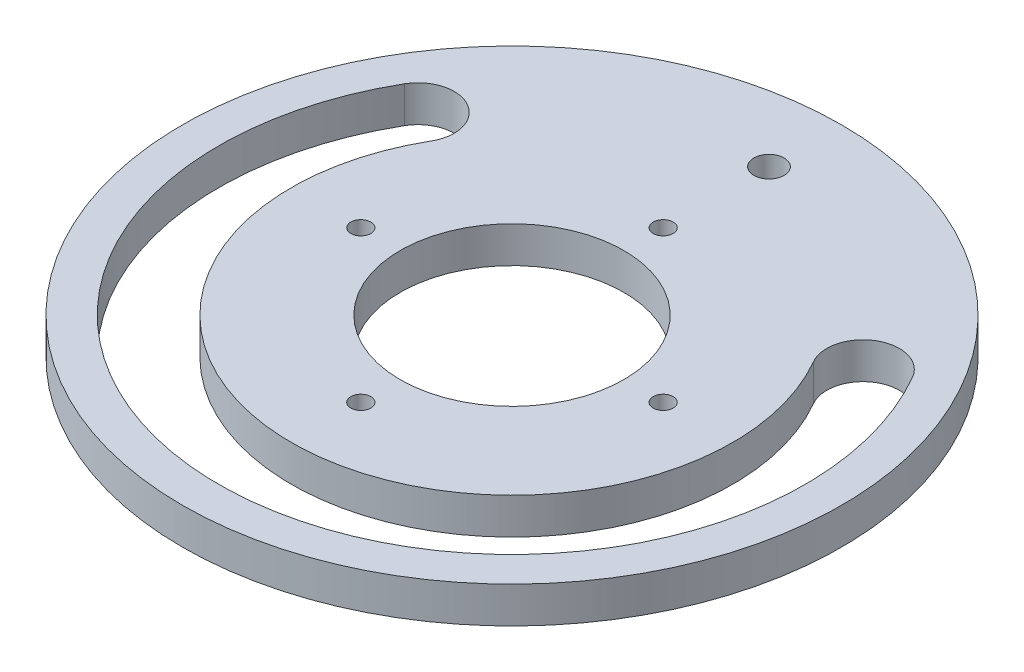
SolidWorks part; units mm, degrees
ref_plane "Спереди" through (0, 0, 0) normal (0, 0, 1) x (1, 0, 0)
ref_plane "Сверху" through (0, 0, 0) normal (0, 1, 0) x (1, 0, 0)
ref_plane "Справа" through (0, 0, 0) normal (1, 0, 0) x (0, 0, -1)
sketch "Эскиз1" plane through (0, 0, 0) normal (0, 1, 0) x (1, 0, 0)
  circle A0 centre (0, 0) radius 54.5
  dimension "D1" = 109
extrude "Бобышка-Вытянуть1" add sketch "Эскиз1" along normal blind 6
sketch "Эскиз2" plane through (0, 6, 0) normal (0, 1, 0) x (1, 0, 0)
  line L0 (0, 0) -> (0, -54.5) construction
  line L1 (0, 0) -> (-54.5, 0) construction
  line L2 (-54.5, 0) -> (54.5, 0) construction
  line L3 (0, 0) -> (-36.8061, 21.25) construction
  line L4 (0, 54.5) -> (0, 0) construction
  line L5 (0, 0) -> (36.8061, 21.25) construction
  circle A0 centre (0, 0) radius 42.5 construction
  circle A1 centre (0, 0) radius 54.5 construction
  arc A2 (-42.0022, 24.25) -> (42.0022, 24.25) centre (0, 0) ccw
  arc A3 (-31.6099, 18.25) -> (31.6099, 18.25) centre (0, 0) ccw
  circle A4 centre (0, 42.5) radius 2.5
  arc A5 (-31.6099, 18.25) -> (-42.0022, 24.25) centre (-36.8061, 21.25) ccw
  arc A6 (42.0022, 24.25) -> (31.6099, 18.25) centre (36.8061, 21.25) ccw
  dimension "D1" = 85
  dimension "D2" = 5
  dimension "D3" = 97
  dimension "D4" = 73
  dimension "D7" = 12
  dimension "D8" = 12
  dimension "D5" = 120
  dimension "D6" = 60
extrude "Вырез-Вытянуть1" cut sketch "Эскиз2" against normal blind 6
sketch "Эскиз3" plane through (0, 6, 0) normal (0, 1, 0) x (1, 0, 0)
  line L0 (0, 54.5) -> (0, -54.5) construction
  line L1 (0, -54.5) -> (54.5, 0) construction
  line L2 (54.5, 0) -> (-54.5, 0) construction
  circle A0 centre (0, 0) radius 18.5
  circle A1 centre (0, 0) radius 54.5 construction
  circle A2 centre (0, 0) radius 25 construction
  circle A3 centre (0, 25) radius 1.65
  circle A4 centre (-25, 0) radius 1.65
  circle A5 centre (0, -25) radius 1.65
  circle A6 centre (25, 0) radius 1.65
  dimension "D1" = 37
  dimension "D2" = 50
  dimension "D3" = 3.3
  dimension "D4" = 3.3
  dimension "D5" = 3.3
  dimension "D6" = 3.3
extrude "Вырез-Вытянуть2" cut sketch "Эскиз3" against normal blind 6
